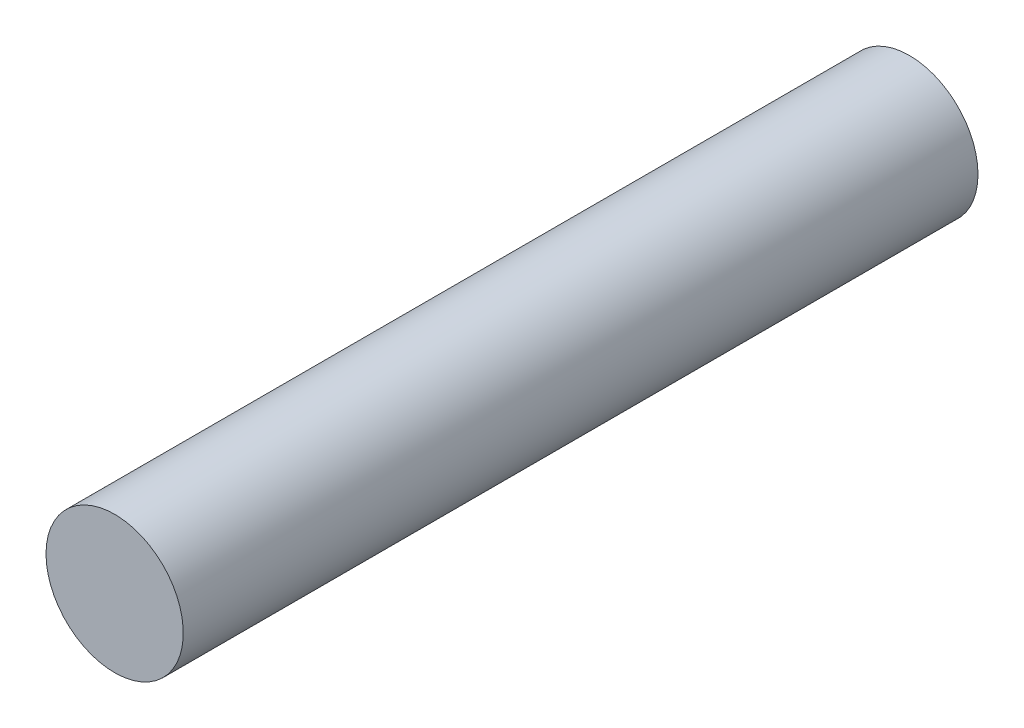
SolidWorks part; units mm, degrees
material "AISI 316 Stainless Steel Sheet (SS)"
ref_plane "Front" through (0, 0, 0) normal (0, 0, 1) x (1, 0, 0)
ref_plane "Top" through (0, 0, 0) normal (0, 1, 0) x (1, 0, 0)
ref_plane "Right" through (0, 0, 0) normal (1, 0, 0) x (0, 0, -1)
sketch "Sketch1" plane through (0, 0, 0) normal (0, 0, 1) x (1, 0, 0)
  circle A0 centre (0, 0) radius 2.413
  dimension "D1" = 4.826
extrude "Boss-Extrude1" add sketch "Sketch1" along normal mid plane 133
sketch "Sketch2" plane through (0, 0, 66.5) normal (0, 0, 1) x (1, 0, 0)
  line L1 (-2.413, 1.905) -> (2.413, 1.905)
  line L2 (-2.413, 1.905) -> (-2.413, 2.413)
  line L3 (-2.413, 2.413) -> (2.413, 2.413)
  line L4 (2.413, 1.905) -> (2.413, 2.413)
  line L5 (-2.413, 1.905) -> (2.413, 2.413) construction
  line L6 (-2.413, 2.413) -> (2.413, 1.905) construction
  circle A0 centre (0, 0) radius 2.413 construction
  point P0 (0, 2.159)
  dimension "D1" = 0.508
extrude "Cut-Extrude1" cut sketch "Sketch2" against normal blind 6
sketch "Sketch3" plane through (0, 0, 0) normal (0, 1, 0) x (1, 0, 0)
  line L0 (-2.413, 66.5) -> (-2.413, -66.5) construction
  line L1 (-2.413, 38.56) -> (2.413, 38.56)
  line L2 (-2.413, 38.56) -> (-2.413, -66.5)
  line L3 (-2.413, -66.5) -> (2.413, -66.5)
  line L4 (2.413, 38.56) -> (2.413, -66.5)
  line L5 (2.413, 66.5) -> (-2.413, 66.5) construction
  point P7 (-2.413, 49.8335)
  dimension "D1" = 27.94
extrude "Cut-Extrude2" cut sketch "Sketch3" against normal through all both and the other way through all
